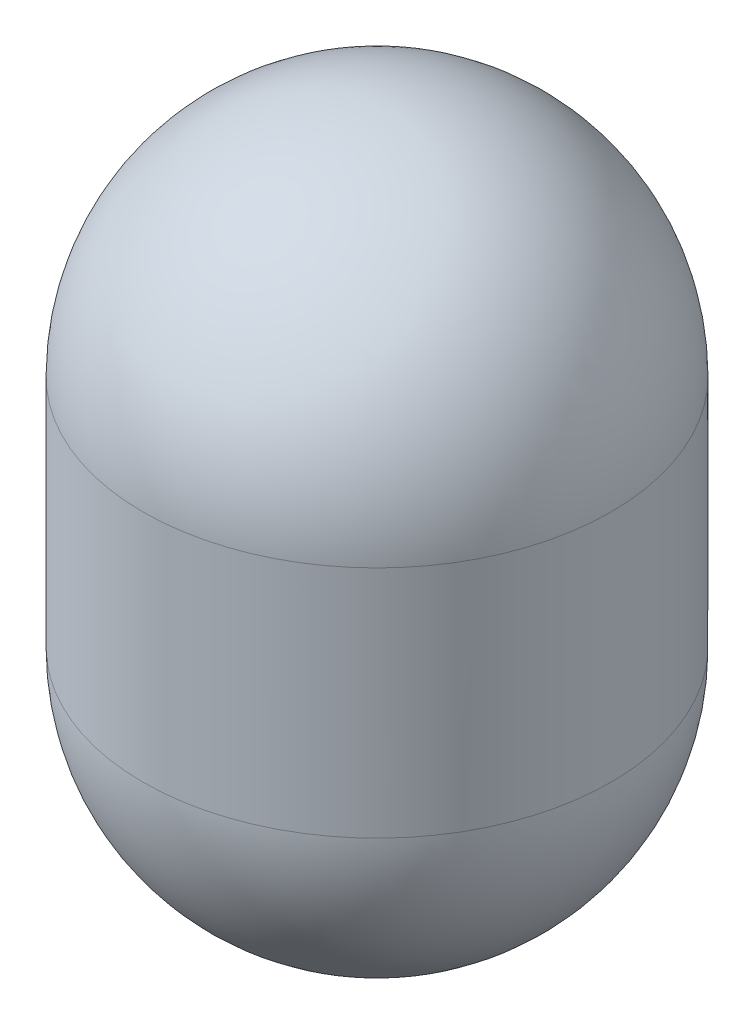
SolidWorks part; units mm, degrees
ref_plane "Front Plane" through (0, 0, 0) normal (0, 0, 1) x (1, 0, 0)
ref_plane "Top Plane" through (0, 0, 0) normal (0, 1, 0) x (1, 0, 0)
ref_plane "Right Plane" through (0, 0, 0) normal (1, 0, 0) x (0, 0, -1)
sketch "Sketch1" plane through (0, 0, 0) normal (0, 0, 1) x (1, 0, 0)
  line L0 (-303, 0) -> (-303, -303)
  line L1 (0, 0) -> (0, -372.8629) construction
  line L2 (0, 303) -> (0, 299)
  line L3 (-299, 0) -> (-299, -303)
  line L4 (0, -602) -> (0, -606)
  arc A0 (0, 303) -> (-303, 0) centre (0, 0) ccw
  arc A1 (-303, -303) -> (0, -606) centre (0, -303) ccw
  arc A2 (0, 299) -> (-299, 0) centre (0, 0) ccw
  arc A3 (-299, -303) -> (0, -602) centre (0, -303) ccw
revolve "Revolve1" add sketch "Sketch1" angle 360 about L1
